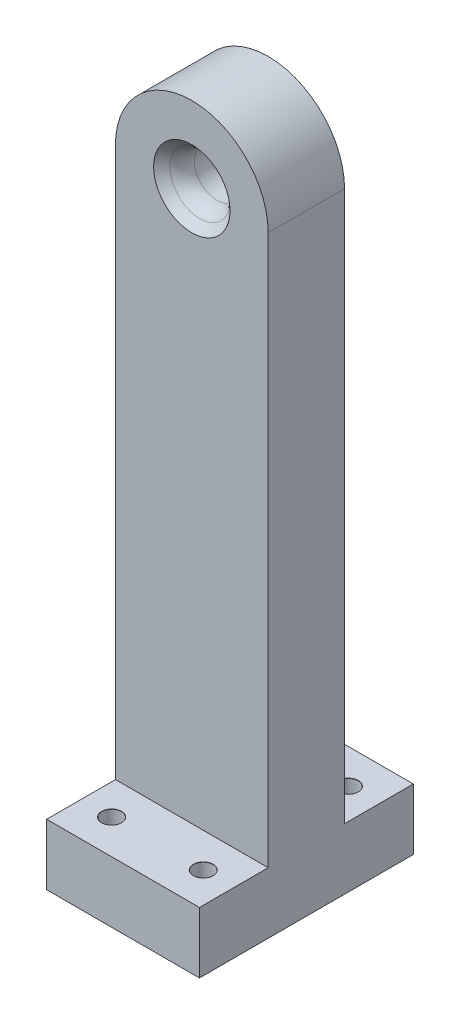
SolidWorks part; units mm, degrees
ref_plane "Front Plane" through (0, 0, 0) normal (0, 0, 1) x (1, 0, 0)
ref_plane "Top Plane" through (0, 0, 0) normal (0, 1, 0) x (1, 0, 0)
ref_plane "Right Plane" through (0, 0, 0) normal (1, 0, 0) x (0, 0, -1)
sketch "Sketch1" plane through (0, 0, 0) normal (0, 0, 1) x (1, 0, 0)
  line L0 (0, 0) -> (-12.5, 0)
  line L1 (-12.5, 0) -> (-12.5, 100)
  line L3 (12.5, 100) -> (12.5, 0)
  line L4 (12.5, 0) -> (0, 0)
  line L5 (0, 0) -> (0, 100) construction
  arc A0 (-12.5, 100) -> (12.5, 100) centre (0, 100) cw
  circle A1 centre (0, 100) radius 3.75
  dimension "D5" = 7.5
  dimension "D1" = 25
  dimension "D2" = 100
extrude "Boss-Extrude1" add sketch "Sketch1" along normal blind 35
sketch "Sketch5" plane through (12.5, 0, 0) normal (1, 0, 0) x (0, 0, -1)
  line L0 (-35, 0) -> (-35, 100) construction
  line L1 (-35, 10) -> (-23.75, 10)
  line L2 (-35, 10) -> (-35, 112.5)
  line L3 (-35, 112.5) -> (-23.75, 112.5)
  line L4 (-23.75, 10) -> (-23.75, 112.5)
  line L5 (0, 112.5) -> (-35, 112.5) construction
  line L6 (-35, 0) -> (0, 0) construction
  line L8 (0, 0) -> (0, 100) construction
  line L9 (0, 10) -> (-11.25, 10)
  line L10 (0, 10) -> (0, 112.5)
  line L11 (0, 112.5) -> (-11.25, 112.5)
  line L12 (-11.25, 10) -> (-11.25, 112.5)
  dimension "D1" = 10
  dimension "D2" = 12.5
extrude "Cut-Extrude1" cut sketch "Sketch5" against normal through all
sketch "Sketch9" plane through (0, 10, 0) normal (0, 1, 0) x (1, 0, 0)
  line L0 (0, 0) -> (0, -35) construction
  line L1 (-12.5, -35) -> (12.5, -35) construction
  line L3 (-12.5, -29.375) -> (12.5, -29.375) construction
  line L4 (-12.5, -35) -> (-12.5, -23.75) construction
  line L5 (12.5, -35) -> (12.5, -23.75) construction
  line L7 (-12.5, -5.625) -> (12.5, -5.625) construction
  line L8 (-12.5, -11.25) -> (-12.5, 0) construction
  line L9 (12.5, -11.25) -> (12.5, 0) construction
  point P0 (-7.5, -5.625)
  point P2 (7.5, -5.625)
  point P4 (7.5, -29.375)
  point P6 (-7.5, -29.375)
  dimension "D1" = 15
hole_wizard "Ø3.2 (3.2) Diameter Hole1" positions "Sketch9" profile "Sketch8" hole size "Ø3.2" standard "ANSI Metric" end condition through all
sketch "Sketch8" plane through (-7.5, 10, 5.625) normal (1, 0, 0) x (0, 0, 1)
  line L0 (0, 0) -> (0, 10)
  line L1 (0, 10) -> (1.6, 10)
  line L2 (1.6, 10) -> (1.6, 0.025)
  line L3 (1.6, 0.025) -> (1.625, 0)
  line L5 (1.625, 0) -> (0, 0)
  line L6 (-1.6, 0.025) -> (-1.625, 0) construction
  line L11 (0, -6.35) -> (0, 107.95) construction
  dimension "Thru Hole Dia." = 3.2
  dimension "Thru Hole Depth" = 10
  dimension "Near C'Sink Dia." = 3.25
  dimension "Near C'Sink Angle" = 90
chamfer "Chamfer1" distance 2.5 angle 45 1 edges at (-3.75, 100, 23.75)
fillet "Fillet1" radius 4 1 edges at (-3.75, 100, 21.25)
